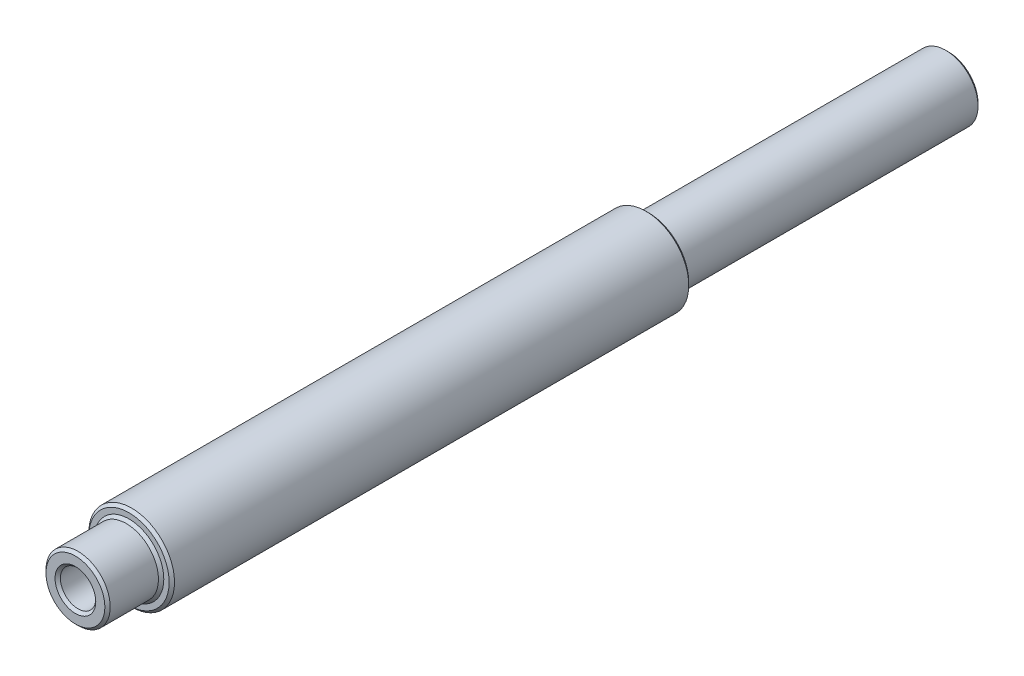
SolidWorks part; units mm, degrees
ref_plane "Plan de face" through (0, 0, 0) normal (0, 0, 1) x (1, 0, 0)
ref_plane "Plan de dessus" through (0, 0, 0) normal (0, 1, 0) x (1, 0, 0)
ref_plane "Plan de droite" through (0, 0, 0) normal (1, 0, 0) x (0, 0, -1)
sketch "Esquisse1" plane through (0, 0, 0) normal (0, 0, 1) x (1, 0, 0)
  circle A0 centre (0, 0) radius 4
  dimension "D1" = 8
extrude "Boss.-Extru.1" add sketch "Esquisse1" along normal blind 81.5
sketch "Esquisse2" plane through (0, 0, 0) normal (1, 0, 0) x (0, 0, -1)
  line L0 (0, 0) -> (-81.5, 0) construction
  line L1 (0, 4) -> (-28, 4)
  line L2 (0, 4) -> (0, 3)
  line L3 (0, 3) -> (-28, 3)
  line L4 (-28, 4) -> (-28, 3)
  line L5 (-81.5, 4) -> (-81.5, -4) construction
  dimension "D1" = 28
  dimension "D2" = 1
revolve "Enlèvement de matière-Révolution1" cut sketch "Esquisse2" angle 360 about L0
sketch "Esquisse3" plane through (0, 0, 0) normal (1, 0, 0) x (0, 0, -1)
  line L0 (-81.5, 0) -> (-75.2074, 0) construction
  line L1 (-81.5, 4) -> (-76.5, 4)
  line L2 (-81.5, 4) -> (-81.5, 3)
  line L3 (-81.5, 3) -> (-76.5, 3)
  line L4 (-76.5, 4) -> (-76.5, 3)
  line L5 (-81.5, 4) -> (-81.5, -4) construction
  dimension "D1" = 1
  dimension "D2" = 5
revolve "Enlèvement de matière-Révolution2" cut sketch "Esquisse3" angle 360 about L0
hole_wizard "Trou taraudé M41" positions "Esquisse4" profile "Esquisse5" tap size "M4" standard "ISO"
sketch "Esquisse4" plane through (0, 0, 81.5) normal (0, 0, 1) x (1, 0, 0)
  point P0 (0, 0)
sketch "Esquisse5" plane through (0, 0, 81.5) normal (1, 0, 0) x (0, -1, 0)
  line L0 (0, 0) -> (0, 12.4914)
  line L1 (0, 12.4914) -> (1.65, 11.5)
  line L2 (1.65, 11.5) -> (1.65, 0)
  line L5 (1.65, 0) -> (0, 0)
  line L10 (0, 12.4914) -> (-1.65, 11.5) construction
  line L11 (0, -6.35) -> (0, 107.95) construction
  dimension "Diamètre du trou pour taraudage" = 3.3
  dimension "Profondeur du trou pour taraudage" = 11.5
  dimension "Angle de pointe" = 118
cosmetic thread "Filetage de perçage1" parameters "D1"=8, "D2"=4
hole_wizard "Trou taraudé M43" positions "Esquisse8" profile "Esquisse9" tap size "M4" standard "ISO" end condition through all
sketch "Esquisse8" plane through (0, 0, 0) normal (0, 0, -1) x (-1, 0, 0)
  point P0 (0, 0)
sketch "Esquisse9" plane through (0, 0, 0) normal (1, 0, 0) x (0, 1, 0)
  line L0 (0, 0) -> (0, 81.5)
  line L1 (0, 81.5) -> (1.65, 81.5)
  line L2 (1.65, 81.5) -> (1.65, 0)
  line L5 (1.65, 0) -> (0, 0)
  line L11 (0, -6.35) -> (0, 107.95) construction
  dimension "Diamètre du trou pour taraudage jusqu'au prochain" = 3.3
  dimension "Profondeur du trou pour taraudage jusqu'au prochain" = 81.5
cosmetic thread "Filetage de perçage3" parameters "D2"=4
chamfer "Chanfrein1" distance 0.25 angle 45 8 edges at (-3, 0, 0) (-3, 0, 28) (-4, 0, 28) (3, 0, 81.5) (3, 0, 76.5) (4, 0, 76.5) (1.65, 0, 81.5) (-1.65, 0, 0)
